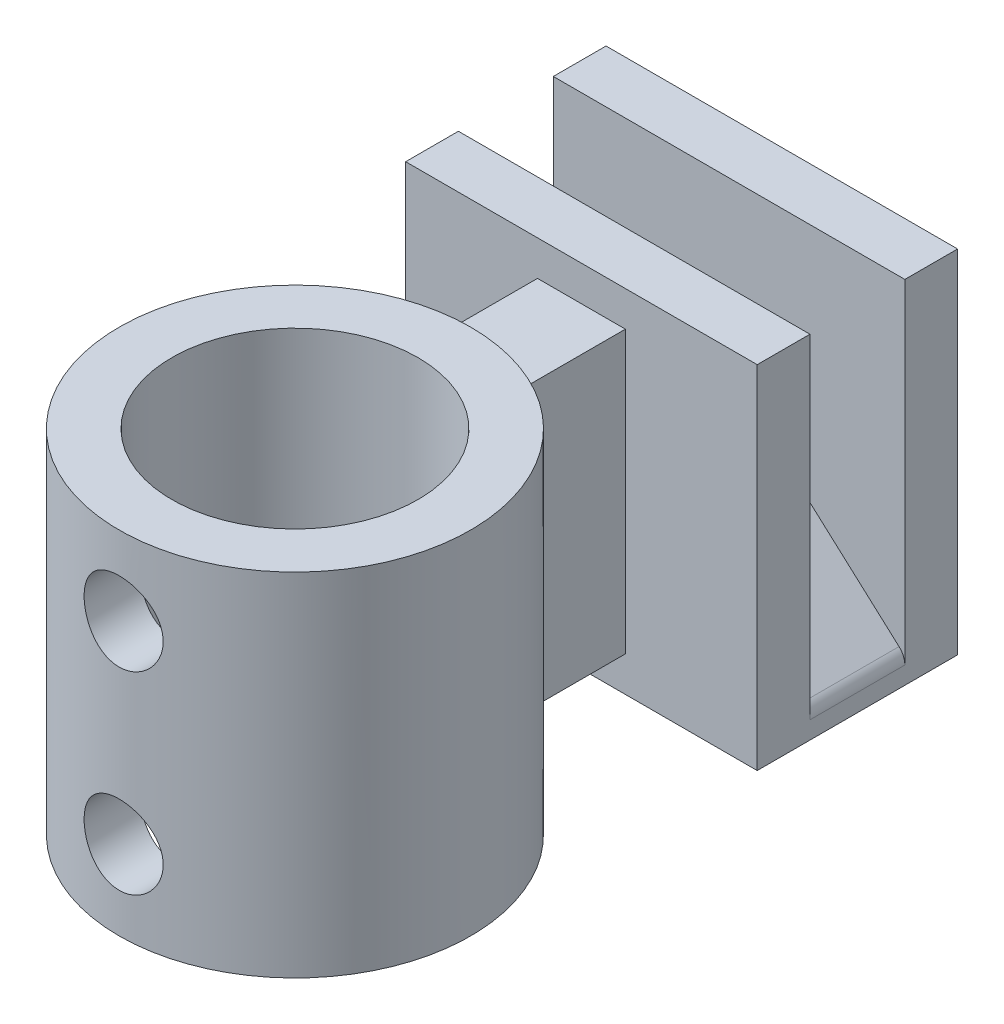
SolidWorks part; units mm, degrees
material "ABS"
ref_plane "Front Plane" through (0, 0, 0) normal (0, 0, 1) x (1, 0, 0)
ref_plane "Top Plane" through (0, 0, 0) normal (0, 1, 0) x (1, 0, 0)
ref_plane "Right Plane" through (0, 0, 0) normal (1, 0, 0) x (0, 0, -1)
sketch "Sketch2" plane through (0, 0, 0) normal (0, 0, 1) x (1, 0, 0)
  line L1 (-10, -5) -> (10, -5)
  line L2 (-10, -5) -> (-10, 5)
  line L3 (-10, 5) -> (10, 5)
  line L4 (10, -5) -> (10, 5)
  line L5 (-10, -5) -> (10, 5) construction
  line L6 (-10, 5) -> (10, -5) construction
  point P0 (0, 0)
  dimension "D1" = 10
  dimension "D2" = 20
extrude "Boss-Extrude1" add sketch "Sketch2" along normal mid plane 5.4
chamfer "Chamfer1" distance 9.5 angle 42 2 edges at (10, 5, 0) (-10, 5, 0)
fillet "Fillet3" radius 1 4 edges at (-10, -3.5538, 0) (10, -3.5538, 0) (0.5, 5, 0) (-0.5, 5, 0)
sketch "Sketch3" plane through (0, 0, 2.7) normal (0, 0, 1) x (1, 0, 0)
  line L0 (-10, -5) -> (10, -5) construction
  line L1 (-10, 15) -> (10, 15)
  line L2 (-10, 15) -> (-10, -5)
  line L3 (-10, -5) -> (10, -5)
  line L4 (10, 15) -> (10, -5)
  line L5 (-10, 15) -> (10, -5) construction
  line L6 (-10, -5) -> (10, 15) construction
  point P0 (0, 5)
  dimension "D1" = 20
  dimension "D2" = 20
extrude "Boss-Extrude2" add sketch "Sketch3" along normal blind 3
mirror "Mirror1" about plane through (0, 0, 0) normal (0, 0, 1) of "Boss-Extrude2"
sketch "Sketch6" plane through (0, 0, 0) normal (0, 1, 0) x (1, 0, 0)
  circle A0 centre (0, -22) radius 10
  circle A1 centre (0, -22) radius 7
  dimension "D1" = 14
  dimension "D2" = 3
  dimension "D3" = 22
extrude "Boss-Extrude3" add sketch "Sketch6" along normal up to surface and the other way up to surface separate body up to face at (0, 15, 4.2) other way up to face at (0, -5, 0)
sketch "Sketch5" plane through (0, 0, 5.7) normal (0, 0, 1) x (1, 0, 0)
  line L0 (-10, -5) -> (10, -5) construction
  line L1 (-2.5, 13) -> (2.5, 13)
  line L2 (-2.5, 13) -> (-2.5, -3)
  line L3 (-2.5, -3) -> (2.5, -3)
  line L4 (2.5, 13) -> (2.5, -3)
  line L5 (-2.5, 13) -> (2.5, -3) construction
  line L6 (-2.5, -3) -> (2.5, 13) construction
  line L7 (10, 15) -> (-10, 15) construction
  point P0 (0, 5)
  dimension "D1" = 2
  dimension "D2" = 2
  dimension "D3" = 5
extrude "Boss-Extrude4" add sketch "Sketch5" along normal up to surface (9.7617 mm away)
ref_plane "Plane1" through (0, 0, 20) normal (0, 0, 1) x (1, 0, 0)
sketch "Sketch7" plane through (0, 0, 20) normal (0, 0, 1) x (1, 0, 0)
  line L2 (-10, -5) -> (10, -5) construction
  line L3 (7, 15) -> (-7, 15) construction
  circle A0 centre (0, 10.5) radius 2.25
  circle A1 centre (0, -0.5) radius 2.25
  dimension "D1" = 4.5
  dimension "D2" = 4.5
  dimension "D3" = 4.5
  dimension "D4" = 4.5
extrude "Cut-Extrude1" cut sketch "Sketch7" along normal up to surface (11.7436 mm away)
equation "\"BEAM_WIDTH\"= 5.4mm"
equation "\"D1@Boss-Extrude1\"=\"BEAM_WIDTH\""
